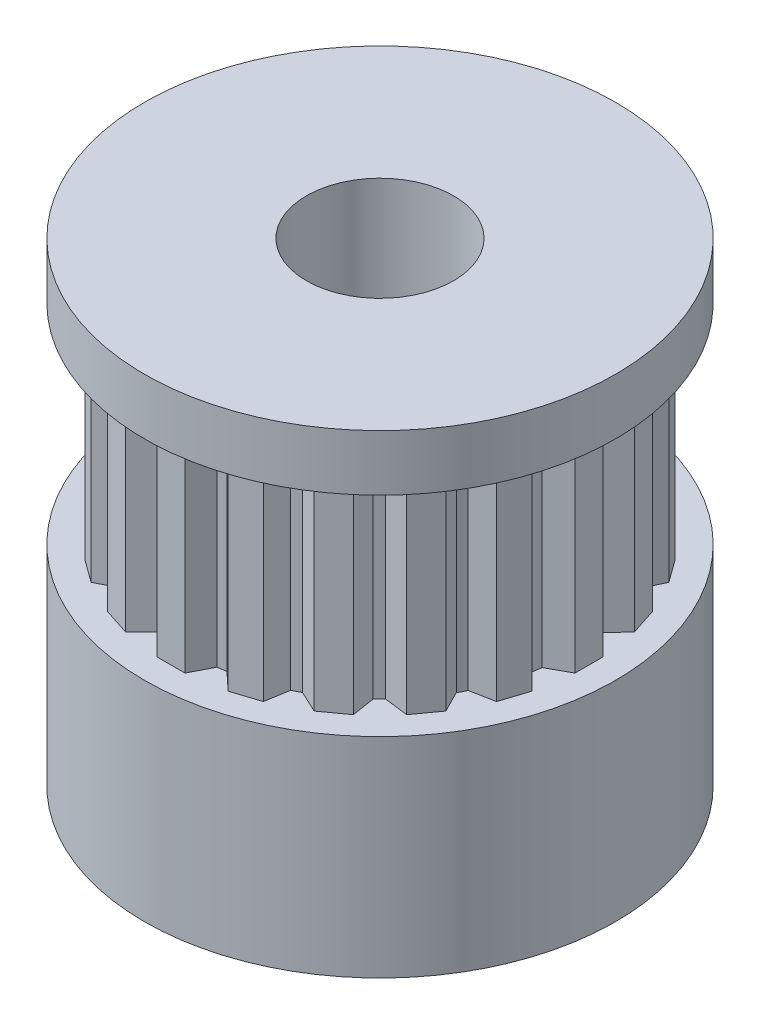
SolidWorks part; units mm, degrees
ref_plane "Front Plane" through (0, 0, 0) normal (0, 0, 1) x (1, 0, 0)
ref_plane "Top Plane" through (0, 0, 0) normal (0, 1, 0) x (1, 0, 0)
ref_plane "Right Plane" through (0, 0, 0) normal (1, 0, 0) x (0, 0, -1)
sketch "Sketch1" plane through (0, 0, 0) normal (0, 1, 0) x (1, 0, 0)
  circle A0 centre (0, 0) radius 8
  dimension "D1" = 16
extrude "Boss-Extrude1" add sketch "Sketch1" along normal blind 7.1
sketch "Sketch2" plane through (0, 7.1, 0) normal (0, 1, 0) x (1, 0, 0)
  line L0 (-0.4757, 7.099) -> (-0.8443, 6.3844)
  line L1 (-0.4757, 7.099) -> (0.4757, 7.099)
  line L2 (0.8734, 6.3805) -> (0.8733, 6.38)
  line L3 (0.4757, 7.099) -> (0.8734, 6.3805)
  line L4 (1.7413, 6.8985) -> (1.17, 6.3329)
  line L5 (1.7413, 6.8985) -> (2.6461, 6.6045)
  line L6 (2.6461, 6.6045) -> (2.8023, 5.7983)
  line L7 (3.7878, 6.0228) -> (3.0697, 5.6614)
  line L8 (3.7878, 6.0228) -> (4.5575, 5.4636)
  line L9 (4.5575, 5.4636) -> (4.457, 4.6486)
  line L10 (5.4636, 4.5575) -> (4.6689, 4.4357)
  line L11 (5.4636, 4.5575) -> (6.0228, 3.7878)
  line L12 (6.0228, 3.7878) -> (5.6753, 3.0438)
  line L14 (6.6045, 2.6461) -> (6.8985, 1.7413)
  line L15 (6.8985, 1.7413) -> (6.3381, 1.141)
  line L16 (7.099, 0.4757) -> (6.3844, 0.8443)
  line L17 (7.099, 0.4757) -> (7.099, -0.4757)
  line L18 (7.099, -0.4757) -> (6.3805, -0.8734)
  line L19 (6.8985, -1.7413) -> (6.3329, -1.17)
  line L20 (6.8985, -1.7413) -> (6.6045, -2.6461)
  line L21 (6.6045, -2.6461) -> (5.7983, -2.8023)
  line L22 (6.0228, -3.7878) -> (5.6614, -3.0697)
  line L23 (6.0228, -3.7878) -> (5.4636, -4.5575)
  line L24 (5.4636, -4.5575) -> (4.6486, -4.457)
  line L25 (4.5575, -5.4636) -> (4.4357, -4.6689)
  line L26 (4.5575, -5.4636) -> (3.7878, -6.0228)
  line L27 (3.7878, -6.0228) -> (3.0438, -5.6753)
  line L28 (2.6461, -6.6045) -> (2.7758, -5.8111)
  line L29 (2.6461, -6.6045) -> (1.7413, -6.8985)
  line L30 (1.7413, -6.8985) -> (1.141, -6.3381)
  line L31 (0.4757, -7.099) -> (0.8443, -6.3844)
  line L32 (0.4757, -7.099) -> (-0.4757, -7.099)
  line L33 (-0.4757, -7.099) -> (-0.8734, -6.3805)
  line L34 (-1.7413, -6.8985) -> (-1.17, -6.3329)
  line L35 (-1.7413, -6.8985) -> (-2.6461, -6.6045)
  line L36 (-2.6461, -6.6045) -> (-2.8023, -5.7983)
  line L37 (-3.7878, -6.0228) -> (-3.0697, -5.6614)
  line L38 (-3.7878, -6.0228) -> (-4.5575, -5.4636)
  line L39 (-4.5575, -5.4636) -> (-4.457, -4.6486)
  line L40 (-5.4636, -4.5575) -> (-4.6689, -4.4357)
  line L41 (-5.4636, -4.5575) -> (-6.0228, -3.7878)
  line L42 (-6.0228, -3.7878) -> (-5.6753, -3.0438)
  line L43 (-6.6045, -2.6461) -> (-5.8111, -2.7758)
  line L44 (-6.6045, -2.6461) -> (-6.8985, -1.7413)
  line L45 (-6.8985, -1.7413) -> (-6.3381, -1.141)
  line L46 (-7.099, -0.4757) -> (-6.3844, -0.8443)
  line L47 (-7.099, -0.4757) -> (-7.099, 0.4757)
  line L48 (-7.099, 0.4757) -> (-6.3805, 0.8734)
  line L49 (-6.8985, 1.7413) -> (-6.3329, 1.17)
  line L50 (-6.8985, 1.7413) -> (-6.6045, 2.6461)
  line L51 (-6.6045, 2.6461) -> (-5.7983, 2.8023)
  line L52 (-6.0228, 3.7878) -> (-5.6614, 3.0697)
  line L53 (-6.0228, 3.7878) -> (-5.4636, 4.5575)
  line L54 (-5.4636, 4.5575) -> (-4.6486, 4.457)
  line L55 (-4.5575, 5.4636) -> (-4.4357, 4.6689)
  line L56 (-4.5575, 5.4636) -> (-3.7878, 6.0228)
  line L57 (-3.7878, 6.0228) -> (-3.0438, 5.6753)
  line L58 (-2.6461, 6.6045) -> (-2.7758, 5.8111)
  line L59 (-2.6461, 6.6045) -> (-1.7413, 6.8985)
  line L60 (-1.7413, 6.8985) -> (-1.141, 6.3381)
  line L61 (0.8733, 6.38) -> (1.17, 6.3329)
  line L62 (5.8198, 2.7744) -> (6.6045, 2.6461)
  line L63 (6.6045, 2.6461) -> (5.8111, 2.7758) [skipped]
  arc A21 (-1.141, 6.3381) -> (-0.8443, 6.3844) centre (0, 0) cw
  arc A22 (-5.7983, 2.8023) -> (-5.6614, 3.0697) centre (-5.0358, 2.5804) cw
  arc A23 (2.8023, 5.7983) -> (3.0697, 5.6614) centre (0, 0) cw
  arc A24 (4.457, 4.6486) -> (4.6689, 4.4357) centre (0, 0) cw
  arc A25 (5.6753, 3.0438) -> (5.8198, 2.7744) centre (4.5506, 2.2672) cw
  arc A26 (6.3381, 1.141) -> (6.3844, 0.8443) centre (0, 0) cw
  arc A27 (6.3805, -0.8734) -> (6.3329, -1.17) centre (0, 0) cw
  arc A28 (5.7983, -2.8023) -> (5.6614, -3.0697) centre (0, 0) cw
  arc A29 (4.6486, -4.457) -> (4.4357, -4.6689) centre (0, 0) cw
  arc A30 (2.7758, -5.8111) -> (3.0438, -5.6753) centre (0, 0) ccw
  arc A31 (0.8443, -6.3844) -> (1.141, -6.3381) centre (0, 0) ccw
  arc A32 (-0.8734, -6.3805) -> (-1.17, -6.3329) centre (0, 0) cw
  arc A33 (-2.8023, -5.7983) -> (-3.0697, -5.6614) centre (0, 0) cw
  arc A34 (-4.457, -4.6486) -> (-4.6689, -4.4357) centre (0, 0) cw
  arc A35 (-5.6753, -3.0438) -> (-5.8111, -2.7758) centre (0, 0) cw
  arc A36 (-6.3381, -1.141) -> (-6.3844, -0.8443) centre (0, 0) cw
  arc A37 (-6.3805, 0.8734) -> (-6.3329, 1.17) centre (0, 0) cw
  arc A38 (-4.6486, 4.457) -> (-4.4357, 4.6689) centre (-2.9921, 3.0058) cw
  arc A39 (-3.0438, 5.6753) -> (-2.7758, 5.8111) centre (-4.1895, 8.2689) ccw
  point P89 (0, 0)
  dimension "D2" = 20
extrude "Boss-Extrude2" add sketch "Sketch2" along normal blind 7.1
sketch "Sketch3" plane through (0, 14.2, 0) normal (0, 1, 0) x (1, 0, 0)
  circle A0 centre (0, 0) radius 8
  dimension "D1" = 16
extrude "Boss-Extrude3" add sketch "Sketch3" along normal blind 1.9
sketch "Sketch4" plane through (0, 16.1, 0) normal (0, 1, 0) x (1, 0, 0)
  circle A0 centre (0, 0) radius 2.5
  dimension "D1" = 5
extrude "Cut-Extrude1" cut sketch "Sketch4" against normal through all both and the other way through all
